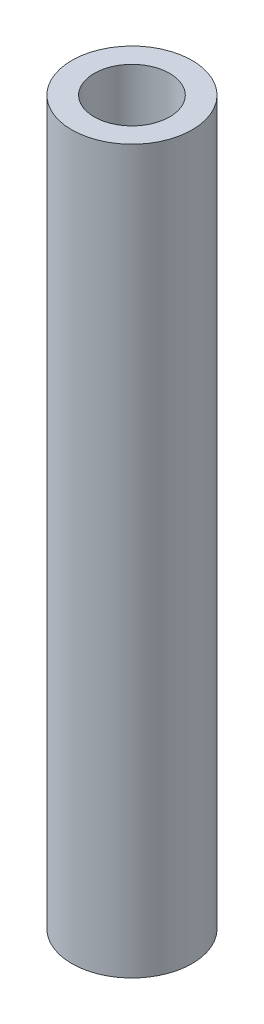
SolidWorks part; units mm, degrees
ref_plane "Front Plane" through (0, 0, 0) normal (1, 0, 0) x (0, 1, 0)
ref_plane "Top Plane" through (0, 0, 0) normal (0, 0, 1) x (0, 1, 0)
ref_plane "Right Plane" through (0, 0, 0) normal (0, 1, 0) x (-1, 0, 0)
sketch "Sketch1" plane through (0, 0, 0) normal (0, 1, 0) x (-1, 0, 0)
  circle A0 centre (0, 0) radius 3.9688
  dimension "D1" = 7.9375
extrude "Boss-Extrude1" add sketch "Sketch1" along normal blind 47.625
sketch "Sketch2" plane through (0, 47.625, 0) normal (0, 1, 0) x (-1, 0, 0)
  point P0 (0, 0)
hole_wizard "#9 (0.196) Diameter Hole1" positions "Sketch2" profile "Sketch3" hole size "#9" standard "ANSI Inch" end condition through all
sketch "Sketch3" plane through (0, 47.625, 0) normal (1, 0, 0) x (0, 0, 1)
  line L0 (0, 0) -> (0, 47.625)
  line L1 (0, 47.625) -> (2.4892, 47.625)
  line L2 (2.4892, 47.625) -> (2.4892, 0)
  line L5 (2.4892, 0) -> (0, 0)
  line L11 (0, -6.35) -> (0, 107.95) construction
  dimension "Thru Hole Dia." = 4.9784
  dimension "Thru Hole Depth" = 47.625
